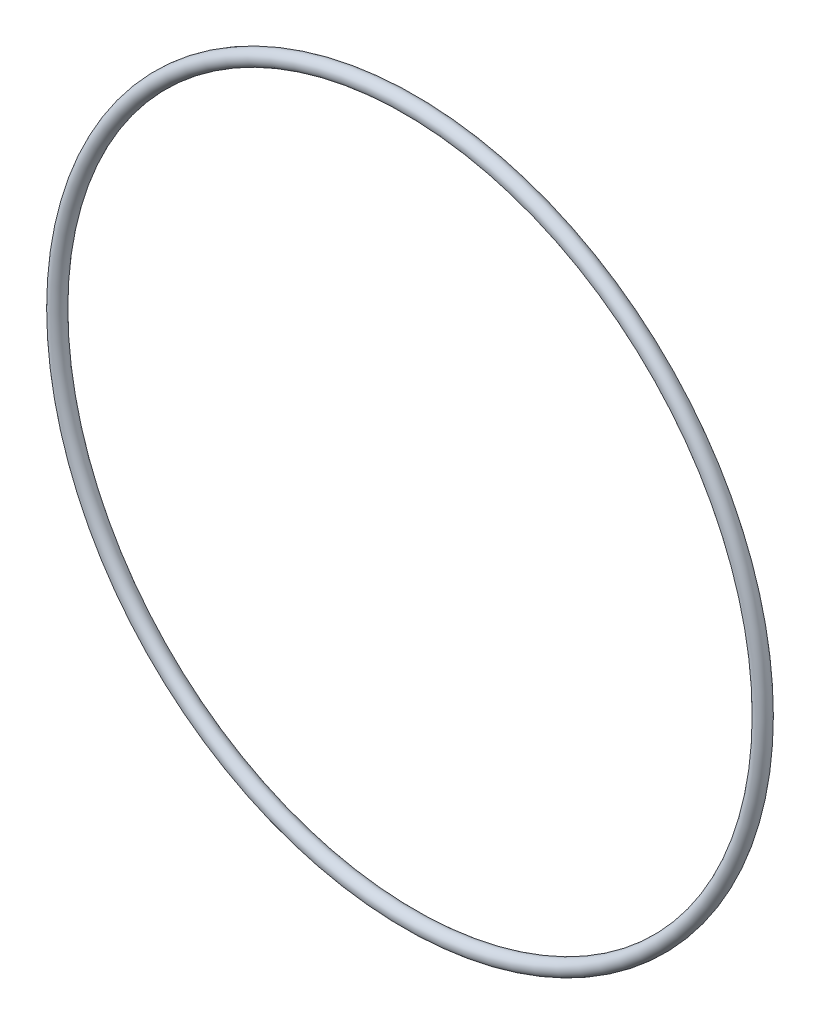
SolidWorks part; units mm, degrees
ref_plane "Front Plane" through (0, 0, 0) normal (0, 0, 1) x (1, 0, 0)
ref_plane "Top Plane" through (0, 0, 0) normal (0, 1, 0) x (1, 0, 0)
ref_plane "Right Plane" through (0, 0, 0) normal (1, 0, 0) x (0, 0, -1)
sketch "Sketch1" plane through (0, 0, 0) normal (0, 0, 1) x (1, 0, 0)
  circle A1 centre (0, 0) radius 62.7761
  circle A2 centre (0, 0) radius 60.1599
  point P4 (0, -62.7761)
  point P5 (0, -60.1599)
  point P6 (0, 60.1599)
  point P7 (0, 62.7761)
  dimension "OD" = 125.5522
  dimension "ID" = 120.3198
  dimension "Width" = 2.6162
sketch "Sketch3" plane through (0, 0, 0) normal (1, 0, 0) x (0, 0, -1)
  line L0 (0, -61.468) -> (-0.654, -62.6008) construction
  line L2 (1.3081, 0) -> (-1.3081, 0) construction
  circle A0 centre (0, -61.468) radius 1.3081
  circle A1 centre (0, 61.468) radius 1.3081 construction
  point P6 (-0.654, -62.6008)
  point P7 (0, -62.7761)
  point P11 (0, 0)
  dimension "D1" = 2.6162
  dimension "D2" = 60
revolve "Revolve1" add sketch "Sketch3" angle 360 about L2
equation "\"D1@Sketch3\"=(\"OD@Sketch1\"-\"ID@Sketch1\")*0.5"
